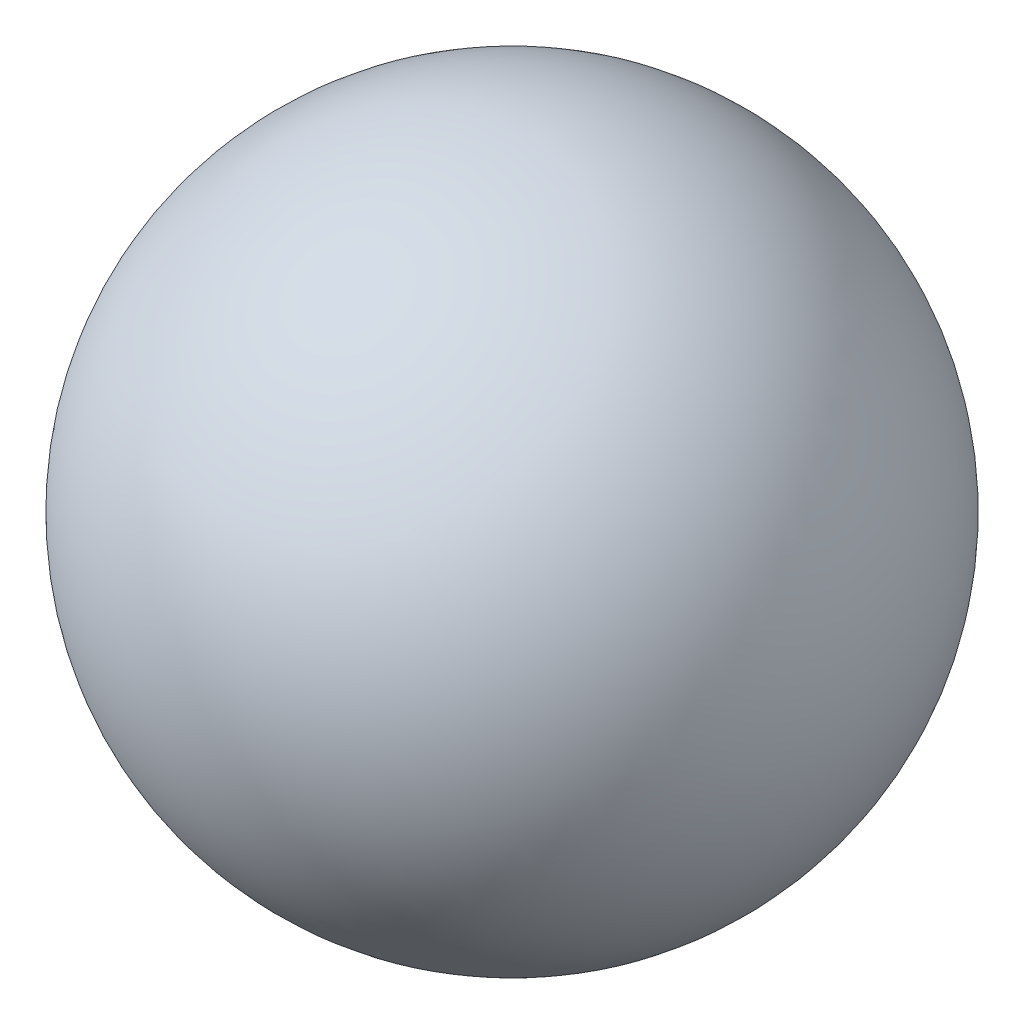
SolidWorks part; units mm, degrees
ref_plane "Front" through (0, 0, 0) normal (0, 0, 1) x (1, 0, 0)
ref_plane "Top" through (0, 0, 0) normal (0, 1, 0) x (1, 0, 0)
ref_plane "Right" through (0, 0, 0) normal (1, 0, 0) x (0, 0, -1)
other "Configuration Table"
sketch "Sketch1" plane through (0, 0, 0) normal (0, 0, 1) x (1, 0, 0)
  line L0 (0, 105.5454) -> (0, -111.7086) construction
  line L1 (0, 1000) -> (0, 800)
  line L2 (0, -800) -> (0, -1000)
  arc A0 (0, 800) -> (0, -800) centre (0, 0) cw
  arc A1 (0, 1000) -> (0, -1000) centre (0, 0) cw
  dimension "D1" = 800
  dimension "D2" = 1000
revolve "Revolve1" add sketch "Sketch1" angle 360 about L0
